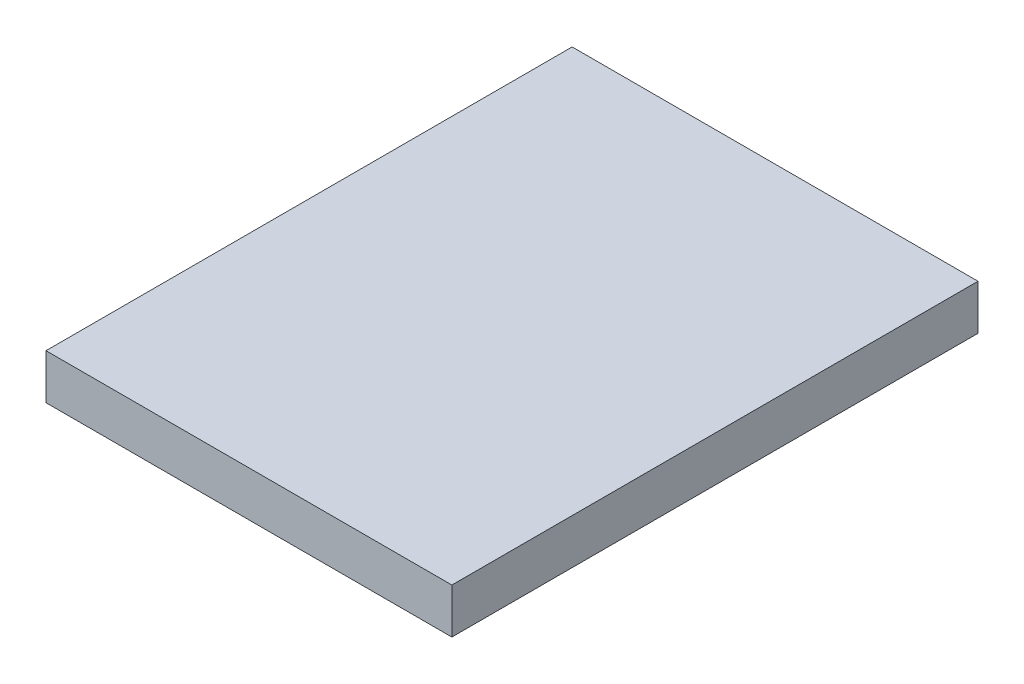
SolidWorks part; units mm, degrees
material "Concreto"
ref_plane "Alzado" through (0, 0, 0) normal (0, 0, 1) x (1, 0, 0)
ref_plane "Planta" through (0, 0, 0) normal (0, 1, 0) x (1, 0, 0)
ref_plane "Vista lateral" through (0, 0, 0) normal (1, 0, 0) x (0, 0, -1)
sketch "Croquis1" plane through (0, 0, 0) normal (0, 1, 0) x (1, 0, 0)
  line L1 (0, 0) -> (2700, 0)
  line L2 (0, 0) -> (0, 3500)
  line L3 (0, 3500) -> (2700, 3500)
  line L4 (2700, 0) -> (2700, 3500)
  dimension "D1" = 2700
  dimension "D2" = 3500
extrude "Saliente-Extruir1" add sketch "Croquis1" along normal blind 300
